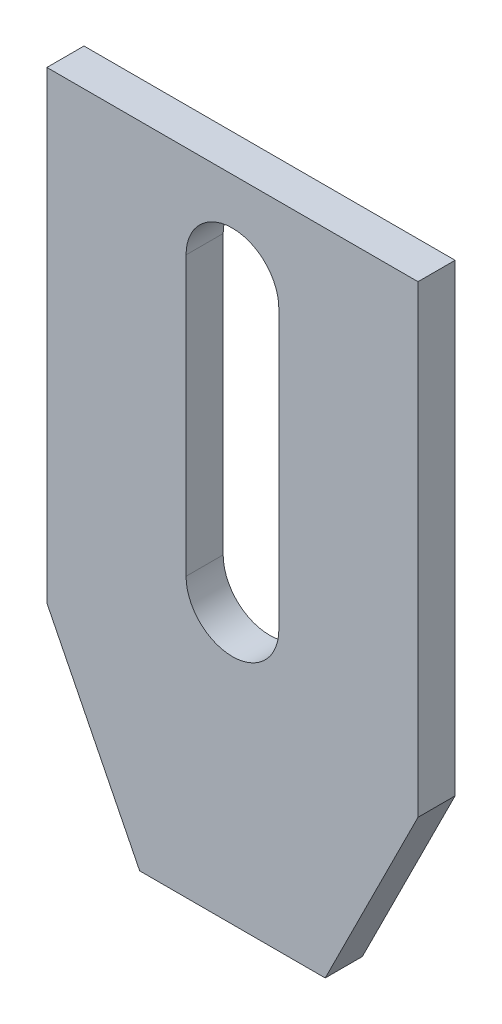
SolidWorks part; units mm, degrees
ref_plane "Front Plane" through (0, 0, 0) normal (0, 0, 1) x (1, 0, 0)
ref_plane "Top Plane" through (0, 0, 0) normal (0, 1, 0) x (1, 0, 0)
ref_plane "Right Plane" through (0, 0, 0) normal (1, 0, 0) x (0, 0, -1)
sketch "Sketch1" plane through (0, 0, 0) normal (0, 0, 1) x (1, 0, 0)
  line L0 (17.9474, 44.2105) -> (-22.0526, 44.2105)
  line L1 (-22.0526, 44.2105) -> (-22.0526, -5.7895)
  line L2 (-22.0526, -5.7895) -> (-12.0526, -25.7895)
  line L3 (-12.0526, -25.7895) -> (7.9474, -25.7895)
  line L4 (7.9474, -25.7895) -> (17.9474, -5.7895)
  line L5 (17.9474, -5.7895) -> (17.9474, 44.2105)
  line L6 (-2.0526, 34.2105) -> (-2.0526, 4.2105) construction
  line L7 (2.9474, 34.2105) -> (2.9474, 4.2105)
  line L8 (-7.0526, 34.2105) -> (-7.0526, 4.2105)
  arc A0 (2.9474, 34.2105) -> (-7.0526, 34.2105) centre (-2.0526, 34.2105) ccw
  arc A1 (-7.0526, 4.2105) -> (2.9474, 4.2105) centre (-2.0526, 4.2105) ccw
  point P8 (-2.0526, 19.2105)
  point P13 (-2.0526, 39.2105)
  dimension "D9" = 30
  dimension "D1" = 40
  dimension "D2" = 70
  dimension "D3" = 50
  dimension "D4" = 50
  dimension "D5" = 20
  dimension "D6" = 10
  dimension "D7" = 5
  dimension "D8" = 10
extrude "Boss-Extrude1" add sketch "Sketch1" along normal blind 4
